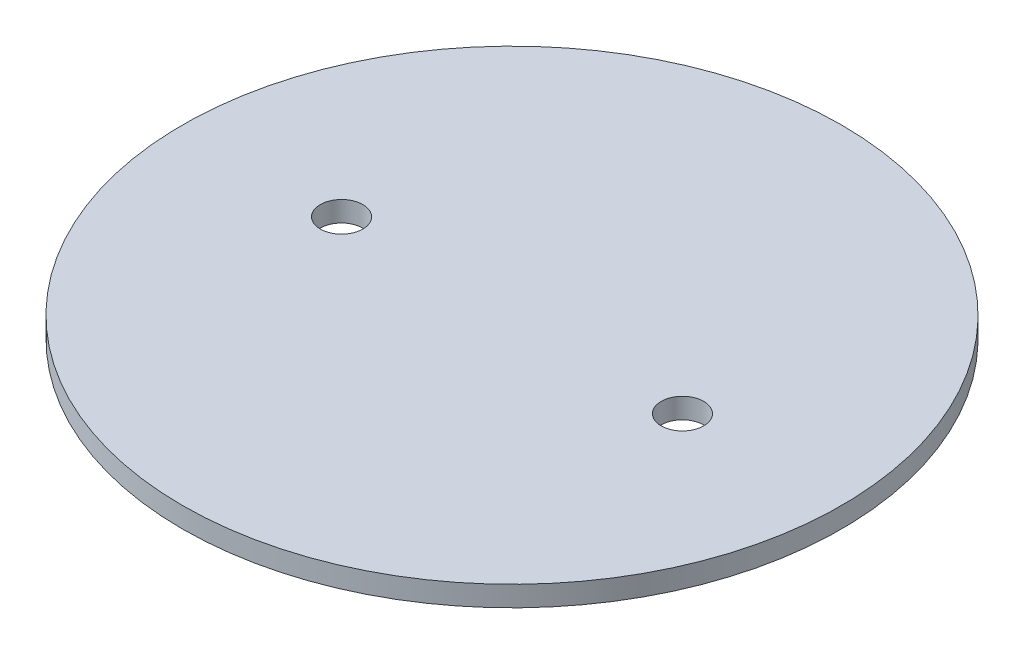
SolidWorks part; units mm, degrees
ref_plane "Front Plane" through (0, 0, 0) normal (0, 0, 1) x (1, 0, 0)
ref_plane "Top Plane" through (0, 0, 0) normal (0, 1, 0) x (1, 0, 0)
ref_plane "Right Plane" through (0, 0, 0) normal (1, 0, 0) x (0, 0, -1)
sketch "Sketch1" plane through (0, 0, 0) normal (0, 1, 0) x (1, 0, 0)
  line L0 (-54.4773, 0) -> (0, 0) construction
  line L1 (0, 0) -> (0, 52.6369) construction
  circle A0 centre (0, 0) radius 96.9
  circle A1 centre (50.115, 0) radius 6.25
  circle A2 centre (-50.115, 0) radius 6.25
  dimension "D1" = 193.8
  dimension "D2" = 12.5
  dimension "D3" = 100.23
extrude "Boss-Extrude1" add sketch "Sketch1" along normal mid plane 6
